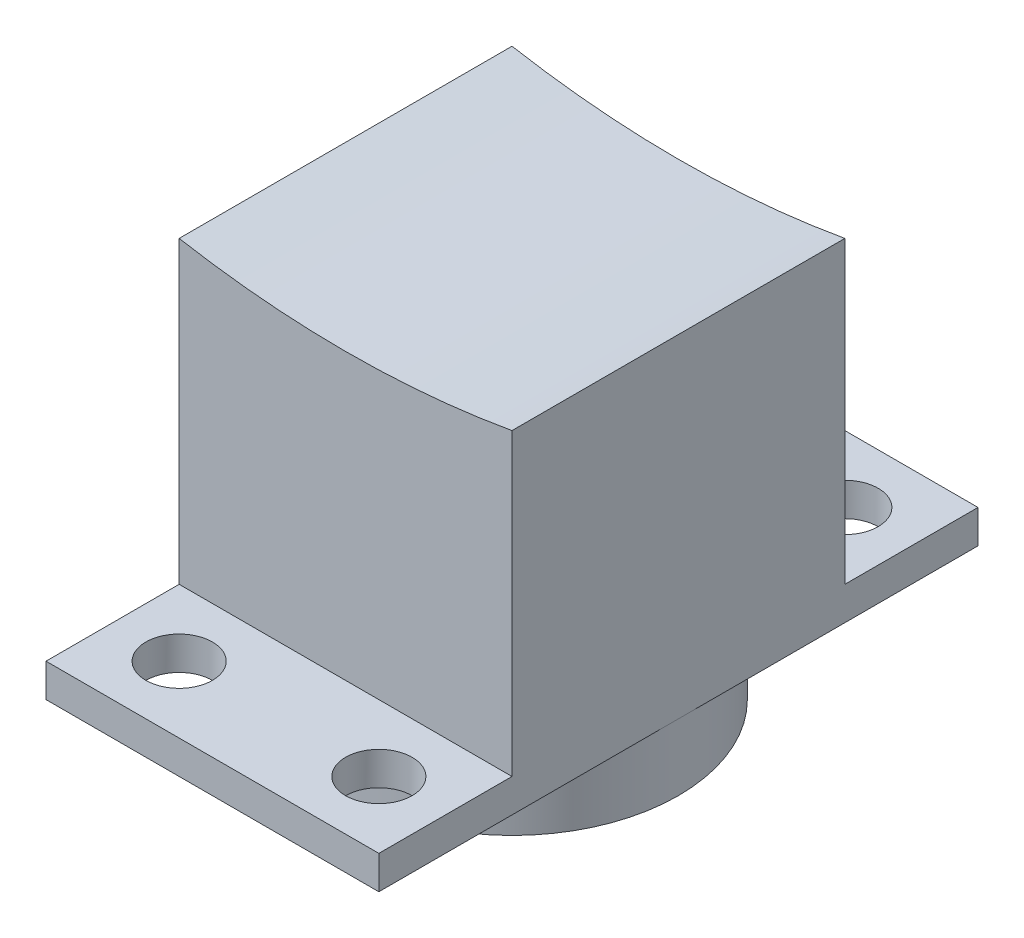
SolidWorks part; units mm, degrees
ref_plane "Front Plane" through (0, 0, 0) normal (0, 0, 1) x (1, 0, 0)
ref_plane "Top Plane" through (0, 0, 0) normal (0, 1, 0) x (1, 0, 0)
ref_plane "Right Plane" through (0, 0, 0) normal (1, 0, 0) x (0, 0, -1)
sketch "Sketch1" plane through (0, 0, 0) normal (0, 0, 1) x (1, 0, 0)
  line L2 (25, 25) -> (25, -25)
  line L3 (25, -25) -> (-25, -25)
  line L4 (-25, 25) -> (-25, -25)
  arc A0 (-25, 25) -> (25, 25) centre (0, 165.3624) ccw
  point P0 (0, 0)
  dimension "D5" = 285.1429
  dimension "D1" = 50
  dimension "D2" = 50
  dimension "D3" = 25
  dimension "D4" = 50
extrude "Boss-Extrude1" add sketch "Sketch1" along normal blind 50
sketch "Sketch2" plane through (0, -25, 0) normal (0, -1, 0) x (1, 0, 0)
  circle A0 centre (0, 25) radius 25
  dimension "D1" = 25
extrude "Boss-Extrude2" add sketch "Sketch2" along normal blind 10
sketch "Sketch3" plane through (0, 0, 50) normal (0, 0, 1) x (1, 0, 0)
  line L0 (25, -25) -> (25, 25) construction
  line L1 (-25, -25) -> (25, -25)
  line L2 (-25, -25) -> (-25, -20)
  line L3 (-25, -20) -> (25, -20)
  line L4 (25, -25) -> (25, -20)
  dimension "D1" = 5
extrude "Boss-Extrude3" add sketch "Sketch3" along normal blind 20 and the other way blind 70
sketch "Sketch4" plane through (0, -20, 0) normal (0, 1, 0) x (1, 0, 0)
  line L0 (25, -70) -> (-25, -70) construction
  line L1 (-25, -50) -> (-25, -70) construction
  line L2 (25, -50) -> (25, -70) construction
  line L4 (25, 20) -> (-25, 20) construction
  circle A0 centre (-15, -60) radius 5
  circle A1 centre (15, -60) radius 5
  circle A2 centre (15, 10) radius 5
  circle A3 centre (-15, 10) radius 5
  dimension "D1" = 10
  dimension "D2" = 10
  dimension "D7" = 10
  dimension "D8" = 10
  dimension "D3" = 10
  dimension "D4" = 10
  dimension "D5" = 10
  dimension "D6" = 10
  dimension "D9" = 10
  dimension "D10" = 10
extrude "Cut-Extrude1" cut sketch "Sketch4" against normal blind 10
equation "\"ThrusterDim\"=160.5mm"
equation "\"hatchHoleDiameter\"=600mm"
equation "\"hullThickness\"=177.1mm"
equation "\"gasketHullInterconnectWidth\"=100mm"
equation "\"collarThickness\"=20mm"
equation "\"hatchTunnelLength\"=200mm"
equation "\"oRingDiameter\"=2mm"
equation "\"boltPatternRadiusInterconnect\"=500mm"
equation "\"interconnectBoltDiameter\"=30mm"
equation "\"hatchShaftDiameter\"=20mm"
equation "\"hatchMinima\"=39.9mm"
equation "\"hullDiameter\"=2240mm"
equation "\"hatchMaxima\"=180mm"
equation "\"bushingFlatHatch\"=15mm"
equation "\"hingePivotDiameter\"=20mm"
equation "\"handleWidth\"=250mm"
equation "\"handleHeight\"=160mm"
equation "\"handleThickness\"=25mm"
equation "\"FrameLength\"=2600mm"
equation "\"FrameMidLength\"=1800mm"
equation "\"TubeOD\"=100mm"
equation "\"FrameBackFlat\"=500mm"
equation "\"TubeWall\"=15.0001mm"
equation "\"TopMemberAngle\"=140deg"
equation "\"FrameHight\"=2500mm"
equation "\"D5@Sketch1\"=2*(\"ThrusterDim\"* 0.85714286 + 5)"
